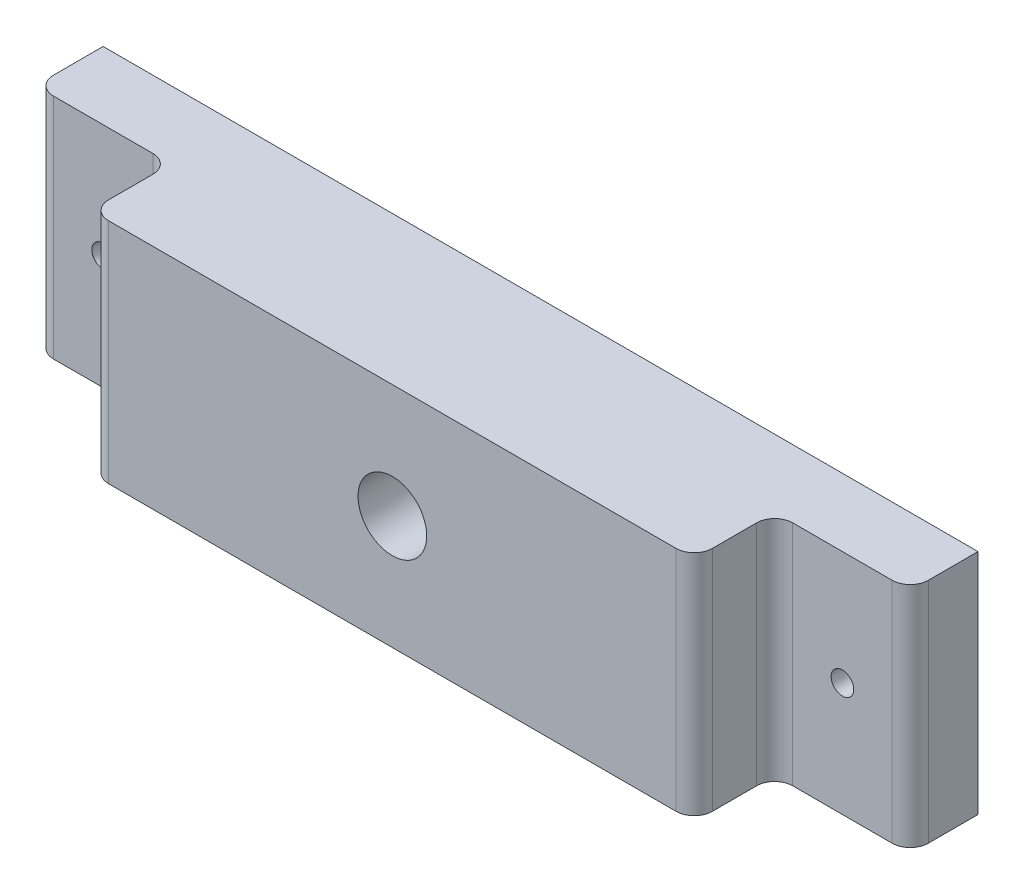
SolidWorks part; units mm, degrees
material "ABS"
ref_plane "Front Plane" through (0, 0, 0) normal (0, 0, 1) x (1, 0, 0)
ref_plane "Top Plane" through (0, 0, 0) normal (0, 1, 0) x (1, 0, 0)
ref_plane "Right Plane" through (0, 0, 0) normal (1, 0, 0) x (0, 0, -1)
sketch "Sketch1" plane through (0, 0, 0) normal (0, 1, 0) x (1, 0, 0)
  line L0 (35.1383, 9.5789) -> (-26.3297, 9.5789)
  line L1 (-26.3297, 9.5789) -> (-26.3297, 4.8164)
  line L2 (-26.3297, 4.8164) -> (-16.8047, 4.8164)
  line L3 (-16.8047, 4.8164) -> (-16.8047, -0.8351)
  line L4 (-16.8047, -0.8351) -> (25.6133, -0.8351)
  line L5 (4.4043, -0.8351) -> (4.4043, 9.5789)
  line L6 (25.6133, 4.8164) -> (25.6133, -0.8351)
  line L7 (35.1383, 4.8164) -> (25.6133, 4.8164)
  line L8 (35.1383, 9.5789) -> (35.1383, 4.8164)
  point P2 (0, 0)
  dimension "D1" = 10.414
  dimension "D2" = 4.7625
  dimension "D3" = 9.525
  dimension "D4" = 21.209
extrude "Boss-Extrude1" add sketch "Sketch1" along normal blind 16.002 contours L4 L5 L0 L1 L2 L3 | L8 L0 L5 L4 L6 L7
fillet "Fillet1" radius 1.27 6 edges at (35.1383, 8.001, -4.8164) (-16.8047, 8.001, -4.8164) (25.6133, 8.001, -4.8164) (25.6133, 8.001, 0.8351) (-16.8047, 8.001, 0.8351) (-26.3297, 8.001, -4.8164)
sketch "Sketch2" plane through (0, 0, 0.8351) normal (0, 0, 1) x (1, 0, 0)
  line L0 (-15.5347, 16.002) -> (24.3433, 16.002) construction
  line L1 (24.3433, 0) -> (24.3433, 16.002) construction
  circle A0 centre (4.4043, 8.001) radius 2.413
  point P4 (4.4043, 16.002)
  point P5 (0, 0)
  point P8 (0, 0)
  point P9 (0, 0)
  point P10 (24.3433, 8.001)
  dimension "D1" = 4.826
extrude "Cut-Extrude1" cut sketch "Sketch2" against normal through all
sketch "Sketch3" plane through (0, 0, -4.8164) normal (0, 0, 1) x (1, 0, 0)
  line L0 (-26.3297, 16.002) -> (-26.3297, 0) construction
  line L1 (-25.0597, 16.002) -> (-18.0747, 16.002) construction
  line L2 (4.4043, 16.002) -> (4.4043, -13.5504) construction
  line L3 (-15.5347, 16.002) -> (24.3433, 16.002) construction
  circle A0 centre (-21.5672, 8.001) radius 0.7937
  circle A1 centre (30.3758, 8.001) radius 0.7937
  point P5 (-26.3297, 8.001)
  point P9 (-21.5672, 16.002)
  dimension "D1" = 1.5875
extrude "Cut-Extrude2" cut sketch "Sketch3" against normal through all
